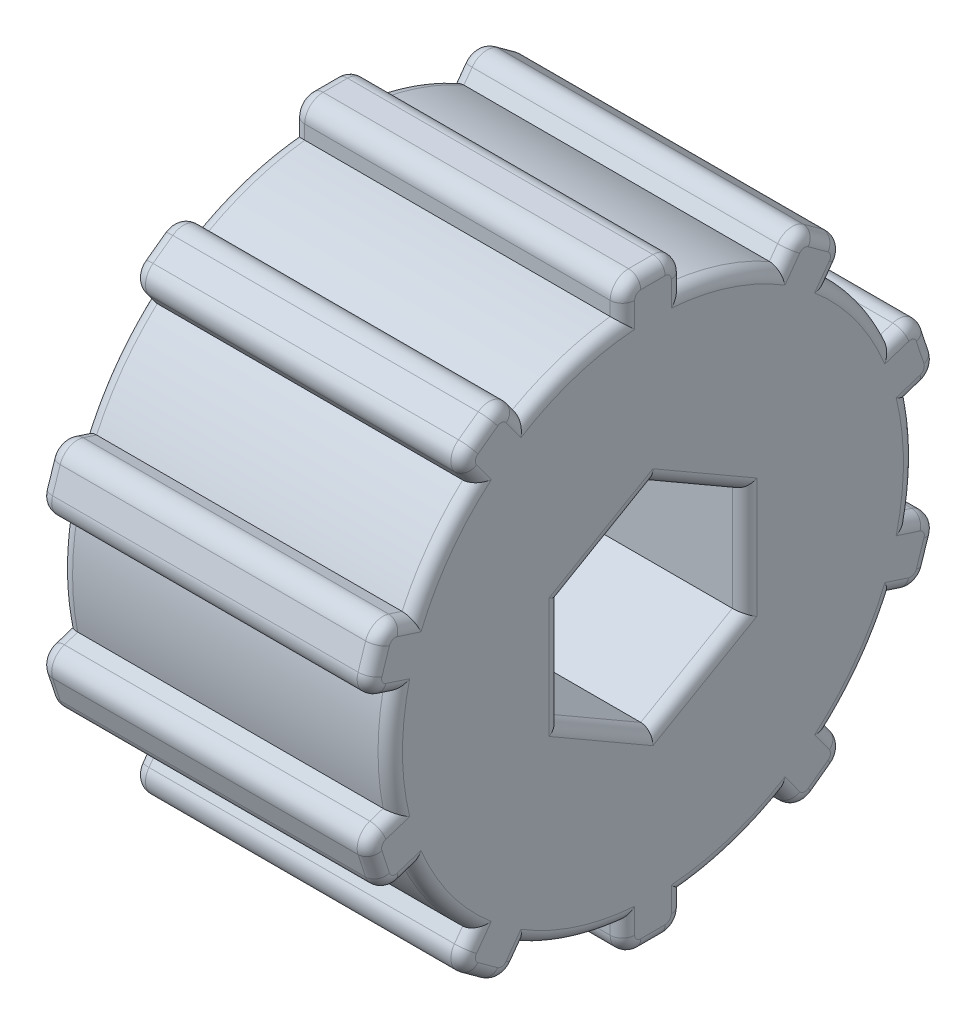
SolidWorks part; units mm, degrees
ref_plane "Alzado" through (0, 0, 0) normal (0, 0, 1) x (1, 0, 0)
ref_plane "Planta" through (0, 0, 0) normal (0, 1, 0) x (1, 0, 0)
ref_plane "Vista lateral" through (0, 0, 0) normal (1, 0, 0) x (0, 0, -1)
sketch "Croquis1" plane through (0, 0, 0) normal (1, 0, 0) x (0, 0, -1)
  circle A0 centre (0, 0) radius 21.5
  point P70 (0.091, 0)
  dimension "D1" = 43
extrude "Saliente-Extruir1" add sketch "Croquis1" along normal blind 27
sketch "Croquis4" plane through (0, 0, 0) normal (-1, 0, 0) x (0, 0, 1)
  line L1 (-2.5, 24) -> (2.5, 24)
  line L2 (-2.5, 24) -> (-2.5, 19)
  line L3 (-2.5, 19) -> (2.5, 19)
  line L4 (2.5, 24) -> (2.5, 19)
  line L5 (-2.5, 24) -> (2.5, 19) construction
  line L6 (-2.5, 19) -> (2.5, 24) construction
  circle A0 centre (0, 0) radius 21.5 construction
  point P0 (0, 21.5)
  dimension "D1" = 5
  dimension "D2" = 5
extrude "Saliente-Extruir2" add sketch "Croquis4" against normal up to surface (27 mm away) up to face at (27, 0, -21.5)
fillet "Redondeo2" radius 1.5 2 edges at (13.5, 24, -2.5) (13.5, 24, 2.5)
pattern_circular "MatrizC1" count 10 over 360 about axis through (0, 0, 0) along (1, 0, 0) of "Saliente-Extruir2", "Redondeo2"
sketch "Croquis5" plane through (0, 0, 0) normal (-1, 0, 0) x (0, 0, 1)
  line L1 (0, -8.6603) -> (7.5, -4.3301)
  line L2 (7.5, -4.3301) -> (7.5, 4.3301)
  line L3 (7.5, 4.3301) -> (0, 8.6603)
  line L4 (0, 8.6603) -> (-7.5, 4.3301)
  line L5 (-7.5, 4.3301) -> (-7.5, -4.3301)
  line L6 (-7.5, -4.3301) -> (0, -8.6603)
  circle A0 centre (0, 0) radius 7.5 construction
  dimension "D1" = 15
extrude "Cortar-Extruir2" cut sketch "Croquis5" against normal up to surface (27 mm away) up to face at (27, 0, 0)
sketch "Croquis6" plane through (0, 0, -7.5) normal (0, 0, 1) x (1, 0, 0)
  line L0 (27, 4.3301) -> (0, 4.3301) construction
  circle A0 centre (14.575, 0) radius 1.1
  point P0 (13.5, 4.3301)
  dimension "D1" = 2.2
  dimension "D2" = 1.075
extrude "Cortar-Extruir3" cut sketch "Croquis6" against normal up to surface (14 mm away)
ref_plane "Plano1" through (0, 0, -21.5) normal (0, 0, -1) x (-1, 0, 0)
sketch "Croquis7" plane through (0, 0, -21.5) normal (0, 0, -1) x (-1, 0, 0)
  circle A0 centre (-14.575, 0) radius 2.25
  dimension "D1" = 4.5
extrude "Cortar-Extruir4" cut sketch "Croquis7" against normal offset from surface (12 mm away) 2 up to face at (15.675, 0, -7.5)
fillet "Redondeo3" radius 0.3 2 edges at (15.0787, -2.1929, -21.3879) (14.575, 2.25, -9.5)
fillet "Redondeo4" radius 1 132 edges at (0, -12.6374, 17.3939) (27, -12.6374, 17.3939) (27, -9.1535, 20.0813) (0, -9.1535, 20.0813) (0, 20.4477, 6.6439) (0, -20.4477, 6.6439) (27, -20.4477, 6.6439) (27, -19.2088, 10.8659) (0, -19.2088, 10.8659) (27, 20.4477, 6.6439) (0, -20.4477, -6.6439) (27, -20.4477, -6.6439) (27, -21.9271, -2.5) (0, -21.9271, -2.5) (0, -12.6374, -17.3939) (27, -12.6374, -17.3939) (27, -16.2699, -14.911) (0, -16.2699, -14.911) (27, 21.9271, 2.5) (0, 21.9271, 2.5) (0, 0, -21.5) (27, 0, -21.5) (27, -4.3982, -21.6264) (0, -4.3982, -21.6264) (0, 12.6374, -17.3939) (27, 12.6374, -17.3939) (27, 9.1535, -20.0813) (0, 9.1535, -20.0813) (0, 20.4477, -6.6439) (27, 20.4477, -6.6439) (27, 19.2088, -10.8659) (0, 19.2088, -10.8659) (27, 19.4164, 14.1068) (0, 19.4164, 14.1068) (0, 19.2088, 10.8659) (0, 17.8497, 15.5157) (0, 20.2722, 12.1815) (27, 19.2088, 10.8659) (27, 17.8497, 15.5157) (27, 20.2722, 12.1815) (27, 7.4164, 22.8254) (0, 7.4164, 22.8254) (0, 9.1535, 20.0813) (0, 5.3208, 23.0443) (0, 9.2404, 21.7707) (27, 9.1535, 20.0813) (27, 5.3208, 23.0443) (27, 9.2404, 21.7707) (27, -7.4164, 22.8254) (0, -7.4164, 22.8254) (0, -4.3982, 21.6264) (0, -9.2404, 21.7707) (0, -5.3208, 23.0443) (27, -4.3982, 21.6264) (27, -9.2404, 21.7707) (27, 24, 0) (27, -5.3208, 23.0443) (0, 24, 0) (27, -19.4164, 14.1068) (0, -19.4164, 14.1068) (0, -16.2699, 14.911) (0, -20.2722, 12.1815) (0, 21.9271, -2.5) (0, -17.8497, 15.5157) (0, 23.5607, 2.0607) (27, -16.2699, 14.911) (27, -20.2722, 12.1815) (27, -17.8497, 15.5157) (0, 23.5607, -2.0607) (27, -24, 0) (0, -24, 0) (0, -21.9271, 2.5) (0, -23.5607, -2.0607) (0, -23.5607, 2.0607) (27, -21.9271, 2.5) (27, -23.5607, -2.0607) (27, -23.5607, 2.0607) (27, 21.9271, -2.5) (27, 23.5607, 2.0607) (27, -19.4164, -14.1068) (0, -19.4164, -14.1068) (0, -19.2088, -10.8659) (0, -17.8497, -15.5157) (0, -20.2722, -12.1815) (27, -19.2088, -10.8659) (27, -17.8497, -15.5157) (27, -20.2722, -12.1815) (27, 23.5607, -2.0607) (27, -7.4164, -22.8254) (0, -7.4164, -22.8254) (0, -9.1535, -20.0813) (0, -5.3208, -23.0443) (0, -9.2404, -21.7707) (27, -9.1535, -20.0813) (27, -5.3208, -23.0443) (27, -9.2404, -21.7707) (27, 7.4164, -22.8254) (0, 7.4164, -22.8254) (0, 4.3982, -21.6264) (0, 9.2404, -21.7707) (0, 5.3208, -23.0443) (27, 4.3982, -21.6264) (27, 9.2404, -21.7707) (27, 5.3208, -23.0443) (27, 19.4164, -14.1068) (0, 19.4164, -14.1068) (0, 16.2699, -14.911) (0, 20.2722, -12.1815) (0, 17.8497, -15.5157) (27, 16.2699, -14.911) (27, 20.2722, -12.1815) (27, 17.8497, -15.5157) (0, -6.4952, -3.75) (0, -6.4952, 3.75) (0, 0, 7.5) (0, 6.4952, 3.75) (0, 6.4952, -3.75) (0, 0, -7.5) (27, -6.4952, 3.75) (27, 0, 7.5) (27, 6.4952, 3.75) (27, 6.4952, -3.75) (27, 0, -7.5) (27, -6.4952, -3.75) (0, 12.6374, 17.3939) (27, 12.6374, 17.3939) (27, 16.2699, 14.911) (0, 16.2699, 14.911) (0, 0, 21.5) (27, 0, 21.5) (27, 4.3982, 21.6264) (0, 4.3982, 21.6264)
